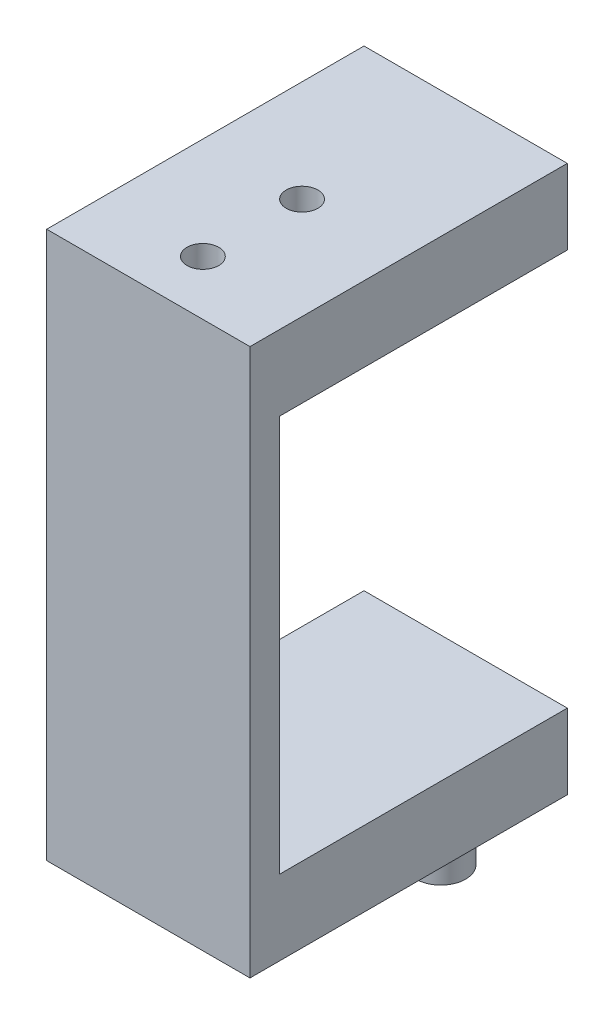
SolidWorks part; units mm, degrees
ref_plane "前视基准面" through (0, 0, 0) normal (0, 0, 1) x (1, 0, 0)
ref_plane "上视基准面" through (0, 0, 0) normal (0, 1, 0) x (1, 0, 0)
ref_plane "右视基准面" through (0, 0, 0) normal (1, 0, 0) x (0, 0, -1)
other "Configuration Table"
sketch "草图1" plane through (0, 0, 0) normal (0, 0, 1) x (1, 0, 0)
  line L0 (-1000, 0) -> (49000, 0) construction
  line L1 (-10.25, -20) -> (10.25, -20)
  line L2 (-10.25, -20) -> (-10.25, 20)
  line L3 (-10.25, 20) -> (10.25, 20)
  line L4 (10.25, -20) -> (10.25, 20)
  line L5 (-10.25, -20) -> (10.25, 20) construction
  line L6 (-10.25, 20) -> (10.25, -20) construction
  line L7 (-5, 15) -> (5, 15)
  line L8 (-5, 15) -> (-5, 25)
  line L9 (-5, 25) -> (5, 25)
  line L10 (5, 15) -> (5, 25)
  line L11 (-5, 15) -> (5, 25) construction
  line L12 (-5, 25) -> (5, 15) construction
  line L14 (-10.25, -35.1417) -> (10.25, -35.1417)
  line L15 (-10.25, -35.1417) -> (-10.25, 35.1417)
  line L16 (-10.25, 35.1417) -> (10.25, 35.1417)
  line L17 (10.25, -35.1417) -> (10.25, 35.1417)
  line L18 (-10.25, -35.1417) -> (10.25, 35.1417) construction
  line L19 (-10.25, 35.1417) -> (10.25, -35.1417) construction
  circle A0 centre (-5, 25) radius 2
  circle A1 centre (5, 25) radius 2
  circle A2 centre (5, -25) radius 2
  circle A3 centre (-5, -25) radius 2
  point P0 (0, 0)
  point P6 (0, 20)
  point P19 (0, 0)
  dimension "D5" = 4
  dimension "D6" = 4
  dimension "D1" = 20.5
  dimension "D2" = 40
  dimension "D3" = 10
  dimension "D4" = 10
extrude "凸台-拉伸1" add sketch "草图1" along normal blind 29 contours A1 L10 L3 L17 L16 L15 L8 A0 L9 | L14 L17 L1 L15 A2 A3 | A1 L9 A0 L8 L3 L10
sketch "草图2" plane through (0, 0, 29) normal (0, 0, 1) x (1, 0, 0)
  line L1 (-10.25, 35.1417) -> (10.25, 35.1417)
  line L2 (-10.25, 35.1417) -> (-10.25, -35.1417)
  line L3 (-10.25, -35.1417) -> (10.25, -35.1417)
  line L4 (10.25, 35.1417) -> (10.25, -35.1417)
extrude "凸台-拉伸2" add sketch "草图2" along normal blind 3
sketch "草图3" plane through (0, 0, 0) normal (0, 0, -1) x (-1, 0, 0)
  line L0 (-10.25, -35.1417) -> (-10.25, -20) construction
  line L1 (-10.25, -27.5709) -> (10.25, -27.5709)
  line L2 (-10.25, -27.5709) -> (-10.25, 27.5709)
  line L3 (-10.25, 27.5709) -> (10.25, 27.5709)
  line L4 (10.25, -27.5709) -> (10.25, 27.5709)
  line L5 (10.25, 20) -> (10.25, 35.1417) construction
  line L7 (-10.25, -35.1417) -> (10.25, -35.1417)
  line L8 (-10.25, -35.1417) -> (-10.25, 35.1417)
  line L9 (-10.25, 35.1417) -> (10.25, 35.1417)
  line L10 (10.25, -35.1417) -> (10.25, 35.1417)
  line M2 (-10.25, -35.1417) -> (10.25, -35.1417)
  line M3 (10.25, -35.1417) -> (10.25, -20)
  line M5 (-10.25, -20) -> (-10.25, -35.1417)
extrude "切除-拉伸1" cut sketch "草图3" against normal through all contours L1 M5 M2 M3 | L3 L10 L9 L8
sketch "草图5" plane through (0, -27.5709, 0) normal (0, -1, 0) x (1, 0, 0)
  line L0 (0, 0) -> (0, 2.5)
  circle A0 centre (0, 2.5) radius 2.5
  dimension "D2" = 5
  dimension "D1" = 2.5
extrude "凸台-拉伸3" add sketch "草图5" along normal blind 10
sketch "草图8" plane through (0, 27.5709, 0) normal (0, 1, 0) x (1, 0, 0)
  line L0 (0, 0) -> (0, -2.5)
  line L1 (0, -2.5) -> (0, -16.5)
  line L2 (0, -16.5) -> (0, -26.5)
  circle A0 centre (0, -16.5) radius 1.6
  circle A1 centre (0, -26.5) radius 1.6
  dimension "D4" = 3.2
  dimension "D5" = 3.2
  dimension "D1" = 2.5
  dimension "D2" = 14
  dimension "D3" = 10
extrude "切除-拉伸2" cut sketch "草图8" against normal up to next
